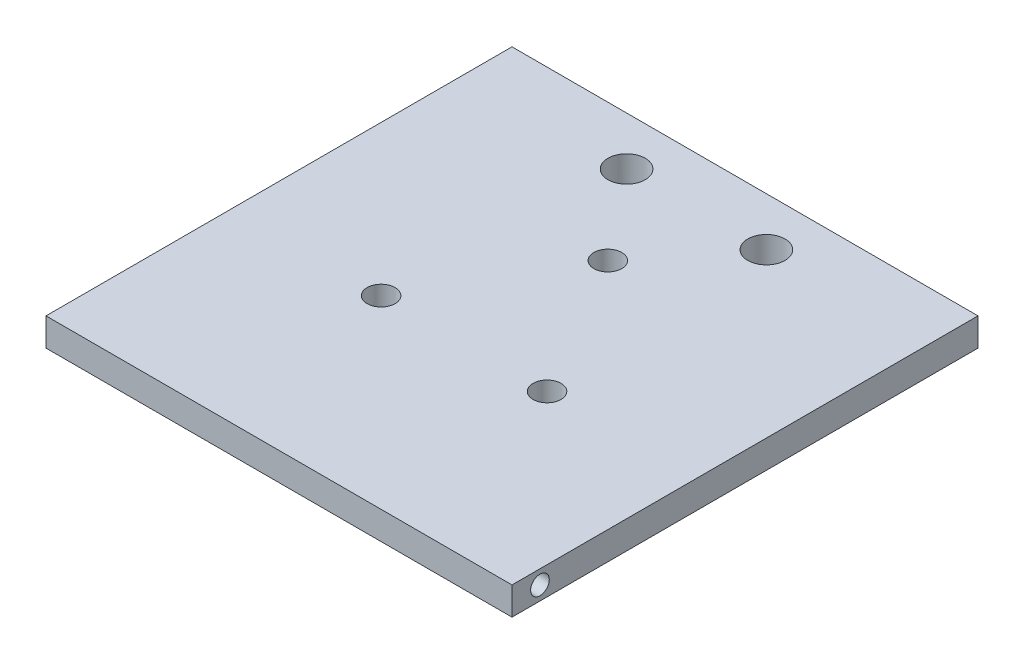
SolidWorks part; units mm, degrees
ref_plane "前视基准面" through (0, 0, 0) normal (0, 0, 1) x (1, 0, 0)
ref_plane "上视基准面" through (0, 0, 0) normal (0, 1, 0) x (1, 0, 0)
ref_plane "右视基准面" through (0, 0, 0) normal (1, 0, 0) x (0, 0, -1)
other "Configuration Table"
sketch "草图1" plane through (0, 0, 0) normal (0, 1, 0) x (1, 0, 0)
  line L1 (-25, -25) -> (25, -25)
  line L2 (-25, -25) -> (-25, 25)
  line L3 (-25, 25) -> (25, 25)
  line L4 (25, -25) -> (25, 25)
  line L5 (-25, -25) -> (25, 25) construction
  line L6 (-25, 25) -> (25, -25) construction
  circle A0 centre (0, 0) radius 10.2795
  circle A1 centre (0, 10.2795) radius 1.5
  circle A2 centre (8.9023, -5.1397) radius 1.5
  circle A3 centre (-8.9023, -5.1397) radius 1.5
  point P0 (0, 0)
  point P17 (0, 0)
  dimension "D3" = 3
  dimension "D1" = 50
  dimension "D2" = 50
  dimension "D4" = 3
extrude "凸台-拉伸1" add sketch "草图1" along normal blind 3 contours L1 L4 L3 L2 A3 A0 A1 A2 | A3 A0 A2 A1
sketch "草图2" plane through (25, 0, 0) normal (1, 0, 0) x (0, 0, -1)
  line L0 (-25, 1.5) -> (-22, 1.5)
  line L1 (-25, 3) -> (-25, 0) construction
  circle A0 centre (-22, 1.5) radius 1
  dimension "D2" = 2
  dimension "D1" = 3
extrude "切除-拉伸2" cut sketch "草图2" against normal through all
sketch "草图4" plane through (0, 0, 0) normal (0, -1, 0) x (1, 0, 0)
  line L0 (-25, 25) -> (25, 25) construction
  line L1 (-15, 30.2051) -> (15, 30.2051)
  line L2 (-15, 30.2051) -> (-15, 19.7949)
  line L3 (-15, 19.7949) -> (15, 19.7949)
  line L4 (15, 30.2051) -> (15, 19.7949)
  line L5 (-15, 30.2051) -> (15, 19.7949) construction
  line L6 (-15, 19.7949) -> (15, 30.2051) construction
  line L7 (0, 30.2051) -> (0, 19.7949)
  line L8 (-1025, 0) -> (48975, 0) construction
  line L9 (-25, 25) -> (-25, -25) construction
  circle A0 centre (-7.5, 19.7949) radius 2
  circle A1 centre (7.5, 19.7949) radius 2
  circle A2 centre (7.5, -19.7949) radius 2
  circle A3 centre (-7.5, -19.7949) radius 2
  point P0 (0, 25)
  point P18 (-25, 0)
  dimension "D3" = 4
  dimension "D1" = 30
  dimension "D2" = 7.5
extrude "切除-拉伸4" cut sketch "草图4" against normal blind 50 contours A3 | A2
